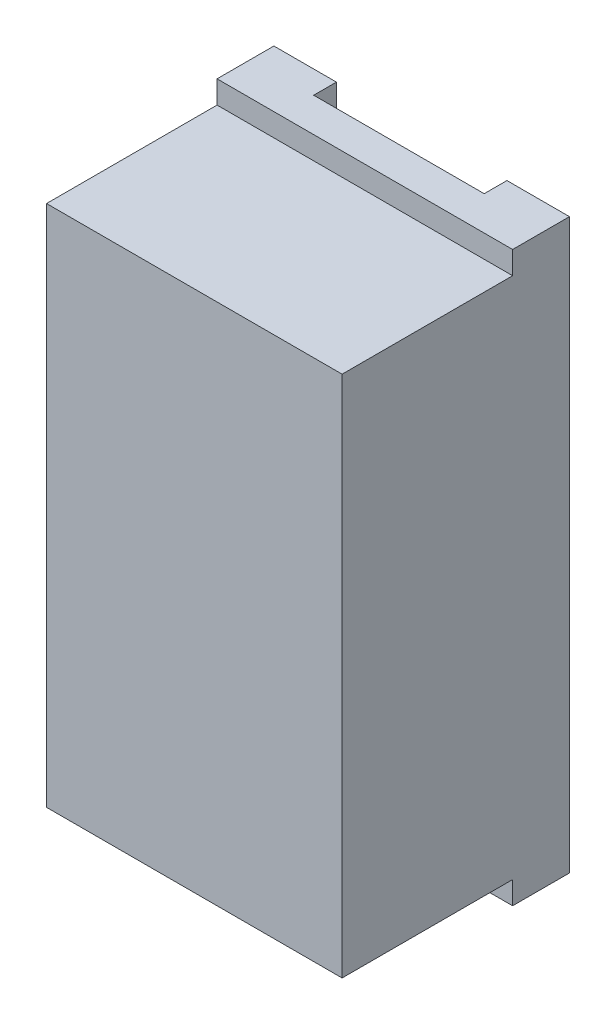
SolidWorks part; units mm, degrees
ref_plane "정면" through (0, 0, 0) normal (0, 0, 1) x (1, 0, 0)
ref_plane "윗면" through (0, 0, 0) normal (0, 1, 0) x (1, 0, 0)
ref_plane "우측면" through (0, 0, 0) normal (1, 0, 0) x (0, 0, -1)
sketch "스케치2" plane through (0, 0, 0) normal (1, 0, 0) x (0, 0, -1)
  line L0 (0, 0) -> (15, 0)
  line L1 (15, 0) -> (15, 2)
  line L2 (15, 2) -> (20, 2)
  line L3 (20, 2) -> (20, -48)
  line L4 (20, -48) -> (15, -48)
  line L5 (15, -48) -> (15, -46)
  line L6 (15, -46) -> (0, -46)
  line L7 (0, -46) -> (0, 0)
  dimension "D1" = 5
  dimension "D2" = 15
  dimension "D3" = 50
  dimension "D4" = 46
extrude "보스-돌출1" add sketch "스케치2" along normal mid plane 26
sketch "스케치4" plane through (0, 0, 0) normal (1, 0, 0) x (0, 0, -1)
  line L1 (18, 6.214) -> (38, 6.214)
  line L2 (18, 6.214) -> (18, -53.786)
  line L3 (18, -53.786) -> (38, -53.786)
  line L4 (38, 6.214) -> (38, -53.786)
  dimension "D1" = 20
  dimension "D2" = 18
  dimension "D3" = 60
extrude "컷-돌출1" cut sketch "스케치4" against normal mid plane 15
